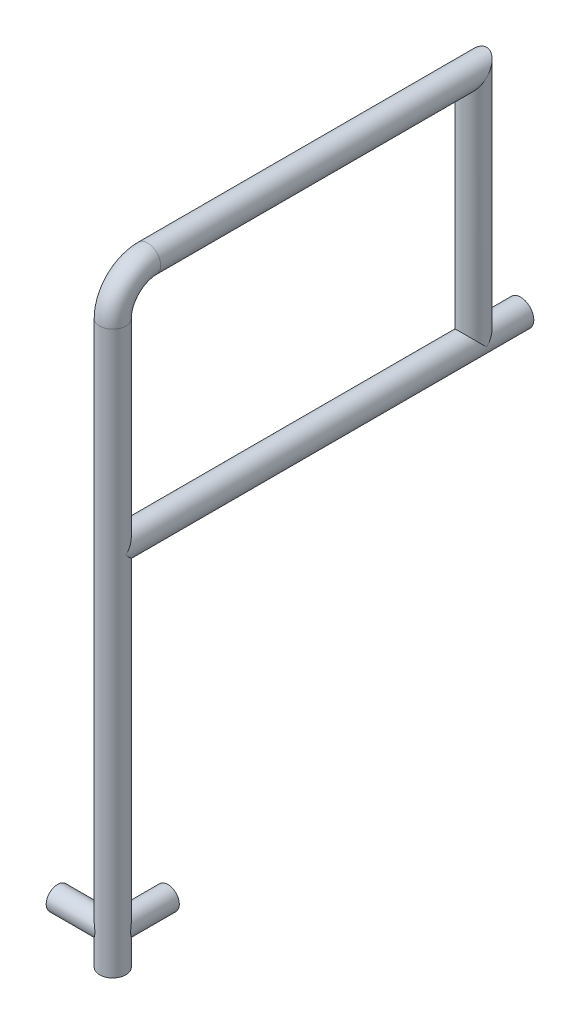
SolidWorks part; units mm, degrees
ref_plane "Front Plane" through (0, 0, 0) normal (0, 0, 1) x (1, 0, 0)
ref_plane "Top Plane" through (0, 0, 0) normal (0, 1, 0) x (1, 0, 0)
ref_plane "Right Plane" through (0, 0, 0) normal (1, 0, 0) x (0, 0, -1)
sketch "Sketch2" plane through (0, 0, 0) normal (0, 1, 0) x (1, 0, 0)
  circle A0 centre (0, 0) radius 20
  dimension "D1" = 40
sketch "Sketch3" plane through (0, 0, 0) normal (1, 0, 0) x (0, 0, -1)
  line L0 (0, 0) -> (0, 302.8198)
  line L1 (53.1445, 355.9643) -> (550.0943, 355.9643)
  line L2 (550.0943, 355.9643) -> (550.0943, 0.0943)
  arc A0 (0, 302.8198) -> (53.1445, 355.9643) centre (53.1445, 302.8198) cw
  dimension "D4" = 53.1445
  dimension "D1" = 550.0943
  dimension "D2" = 355.87
  dimension "D3" = 302.8198
sweep "Sweep1" add profiles "Sketch2" path "Sketch3"
sketch "Sketch4" plane through (0, 0, 0) normal (0, -1, 0) x (1, 0, 0)
  circle A1 centre (0, 0) radius 20
  circle A2 centre (0, 0) radius 20
  dimension "D1" = 0
extrude "Boss-Extrude1" add sketch "Sketch4" along normal blind 553.9061
sketch "Sketch5" plane through (0, 0, 0) normal (0, 0, 1) x (1, 0, 0)
  circle A0 centre (0, 0) radius 20
  dimension "D1" = 40
extrude "Boss-Extrude2" add sketch "Sketch5" against normal blind 622
sketch "Sketch6" plane through (0, 0, -622) normal (0, 0, -1) x (-1, 0, 0)
  line L0 (-20, 0) -> (20, 0) construction
  circle A0 centre (0, 0) radius 17.5
  dimension "D1" = 35
extrude "Cut-Extrude1" cut sketch "Sketch6" against normal blind 199
sketch "Sketch7" plane through (0, 0, 0) normal (0, 0, 1) x (1, 0, 0)
  line L0 (-20, -553.9061) -> (20, -553.9061) construction
  line L1 (0, -553.9061) -> (0, -475.4543) construction
  circle A0 centre (0, -503.9061) radius 17.5
  point P7 (0, -503.9061)
  dimension "D2" = 35
  dimension "D1" = 50
extrude "Boss-Extrude3" add sketch "Sketch7" against normal blind 84
sketch "Sketch9" plane through (0, 0, 0) normal (1, 0, 0) x (0, 0, -1)
  line L0 (84, -503.9061) -> (-43.5432, -503.9061) construction
  line L1 (84, -521.4061) -> (84, -486.4061) construction
  line L2 (0, -553.9061) -> (0, -468.2763) construction
  line L3 (-20, -553.9061) -> (20, -553.9061) construction
  line L4 (0, -468.2763) -> (4.2823, -468.2763) construction
  circle A0 centre (0, -503.9061) radius 17.5
  dimension "D1" = 35
extrude "Boss-Extrude4" add sketch "Sketch9" against normal blind 84
